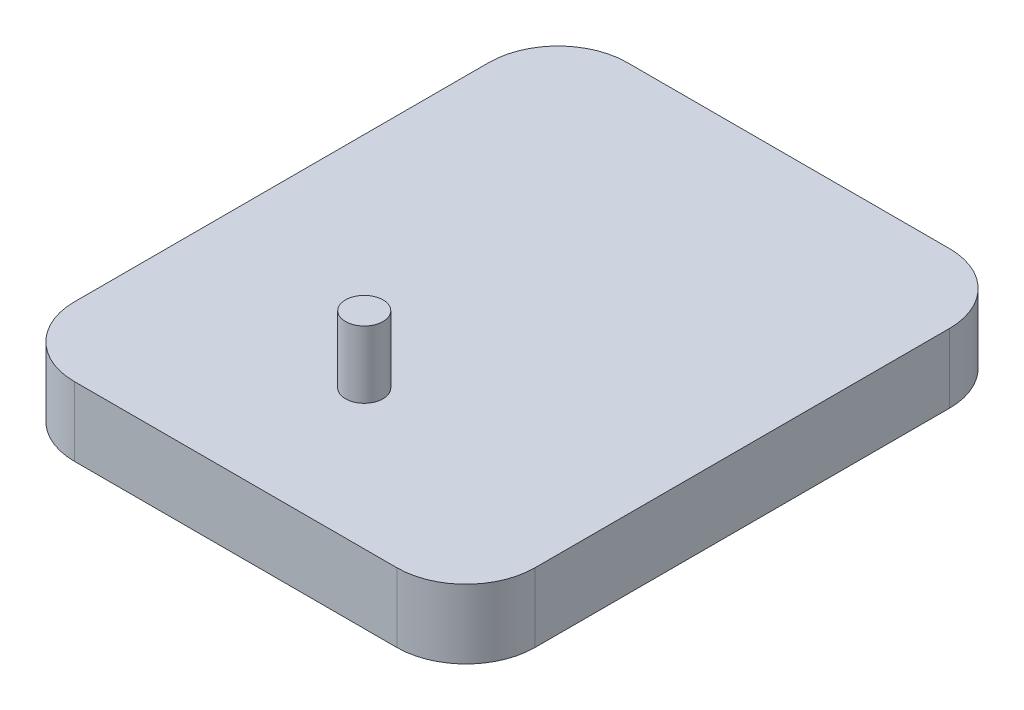
SolidWorks part; units mm, degrees
other "EndMill"
material "Brass"
ref_plane "Front Plane" through (0, 0, 0) normal (0, 0, 1) x (1, 0, 0)
ref_plane "Top Plane" through (0, 0, 0) normal (0, 1, 0) x (1, 0, 0)
ref_plane "Right Plane" through (0, 0, 0) normal (1, 0, 0) x (0, 0, -1)
sketch "Sketch1" plane through (0, 0, 0) normal (0, 1, 0) x (1, 0, 0)
  line L0 (-127, 152.4) -> (127, -152.4) construction
  line L1 (-127, 152.4) -> (127, 152.4)
  line L2 (-127, 152.4) -> (-127, -152.4)
  line L3 (-127, -152.4) -> (127, -152.4)
  line L4 (127, 152.4) -> (127, -152.4)
  dimension "D1" = 254
  dimension "D2" = 304.8
extrude "Boss-Extrude1" add sketch "Sketch1" along normal blind 38.1
fillet "Fillet1" radius 38.1 4 edges at (-127, 19.05, -152.4) (127, 19.05, -152.4) (127, 19.05, 152.4) (-127, 19.05, 152.4)
sketch "Sketch2" plane through (0, 0, 0) normal (0, 0, 1) x (1, 0, 0)
  line L0 (127, 38.1) -> (127, 6.35)
  line L1 (127, 38.1) -> (127, 0) construction
  line L2 (127, 6.35) -> (121.92, 6.35)
  line L3 (121.92, 6.35) -> (121.92, 11.43)
  line L4 (121.92, 11.43) -> (119.38, 11.43)
  line L5 (109.22, 21.59) -> (109.22, 27.94)
  line L6 (109.22, 27.94) -> (104.14, 27.94)
  line L7 (104.14, 27.94) -> (104.14, 31.75)
  line L8 (127, 38.1) -> (88.9, 38.1) construction
  line L9 (97.79, 38.1) -> (127, 38.1)
  line L10 (88.9, 0) -> (127, 0) construction
  arc A0 (119.38, 11.43) -> (109.22, 21.59) centre (119.38, 21.59) cw
  arc A1 (104.14, 31.75) -> (97.79, 38.1) centre (97.79, 31.75) ccw
  dimension "D6" = 6.35
  dimension "D8" = 10.16
  dimension "D1" = 5.08
  dimension "D2" = 6.35
  dimension "D3" = 17.78
  dimension "D4" = 10.16
  dimension "D5" = 22.86
  dimension "D7" = 5.08
sketch "Sketch3" plane through (0, 38.1, 0) normal (0, 1, 0) x (1, 0, 0)
  line L4 (88.9, 152.4) -> (-88.9, 152.4)
  line L5 (-127, 114.3) -> (-127, -114.3)
  line L6 (-88.9, -152.4) -> (88.9, -152.4)
  line L7 (127, -114.3) -> (127, 114.3)
  line L8 (88.9, 152.4) -> (-88.9, 152.4)
  line L9 (-127, 114.3) -> (-127, -114.3)
  line L10 (-88.9, -152.4) -> (88.9, -152.4)
  line L11 (127, -114.3) -> (127, 114.3)
  arc A4 (-88.9, 152.4) -> (-127, 114.3) centre (-88.9, 114.3) ccw
  arc A5 (-127, -114.3) -> (-88.9, -152.4) centre (-88.9, -114.3) ccw
  arc A6 (88.9, -152.4) -> (127, -114.3) centre (88.9, -114.3) ccw
  arc A7 (127, 114.3) -> (88.9, 152.4) centre (88.9, 114.3) ccw
  arc A8 (-88.9, 152.4) -> (-127, 114.3) centre (-88.9, 114.3) ccw
  arc A9 (-127, -114.3) -> (-88.9, -152.4) centre (-88.9, -114.3) ccw
  arc A10 (88.9, -152.4) -> (127, -114.3) centre (88.9, -114.3) ccw
  arc A11 (127, 114.3) -> (88.9, 152.4) centre (88.9, 114.3) ccw
  dimension "D1" = 0
sketch "Sketch4" plane through (0, 0, 0) normal (1, 0, 0) x (0, 0, -1)
  line L1 (-91.8301, 80.9453) -> (-81.4767, 80.9453)
  line L2 (-91.8301, 80.9453) -> (-91.8301, 44.0332)
  line L3 (-91.8301, 44.0332) -> (-81.4767, 44.0332)
  line L4 (-81.4767, 80.9453) -> (-81.4767, 44.0332)
revolve "Revolve1" add sketch "Sketch4" angle 360 about L4
sketch "Sketch5" plane through (0, 0, 0) normal (1, 0, 0) x (0, 0, -1)
  line L0 (-81.4767, 44.0332) -> (28.8135, 14.7299)
  line L1 (-91.8301, 44.0332) -> (-71.1233, 44.0332) construction
ref_plane "Plane1" through (0, 19.05, 0) normal (0, 1, 0) x (1, 0, 0)
sketch "Sketch6" plane through (0, 19.05, 0) normal (0, 1, 0) x (1, 0, 0)
  line L0 (127, 72.8868) -> (57.2444, 72.8868)
  line L1 (127, -114.3) -> (127, 114.3) construction
  line L2 (-98.5928, 20.9163) -> (-98.5928, -80.9942)
  line L3 (-47.8587, -131.7284) -> (46.0085, -131.7284)
  line L4 (96.9356, 20.9163) -> (167.7394, 20.9163)
  arc A0 (57.2444, 72.8868) -> (23.9628, 106.1684) centre (57.2444, 106.1684) cw
  arc A1 (23.9628, 106.1684) -> (-17.3064, 135.4562) centre (-7.0643, 106.1684) ccw
  arc A2 (-17.3064, 135.4562) -> (-98.5928, 20.9163) centre (22.7489, 20.9163) ccw
  arc A3 (-98.5928, -80.9942) -> (-47.8587, -131.7284) centre (-47.8587, -80.9942) ccw
  arc A4 (46.0085, -131.7284) -> (70.9298, -57.0314) centre (46.0085, -90.2226) ccw
  arc A5 (70.9298, -57.0314) -> (96.9356, 20.9163) centre (96.9356, -22.3957) cw
sketch "Sketch7" plane through (127, 0, 0) normal (1, 0, 0) x (0, 0, -1)
  circle A0 centre (72.8868, 19.05) radius 10.9703
sketch "Sketch8" plane through (0, 44.0332, 0) normal (0, -1, 0) x (1, 0, 0)
  circle A1 centre (0, 81.4767) radius 10.3534
  circle A2 centre (0, 81.4767) radius 10.3534
  dimension "D1" = 0
